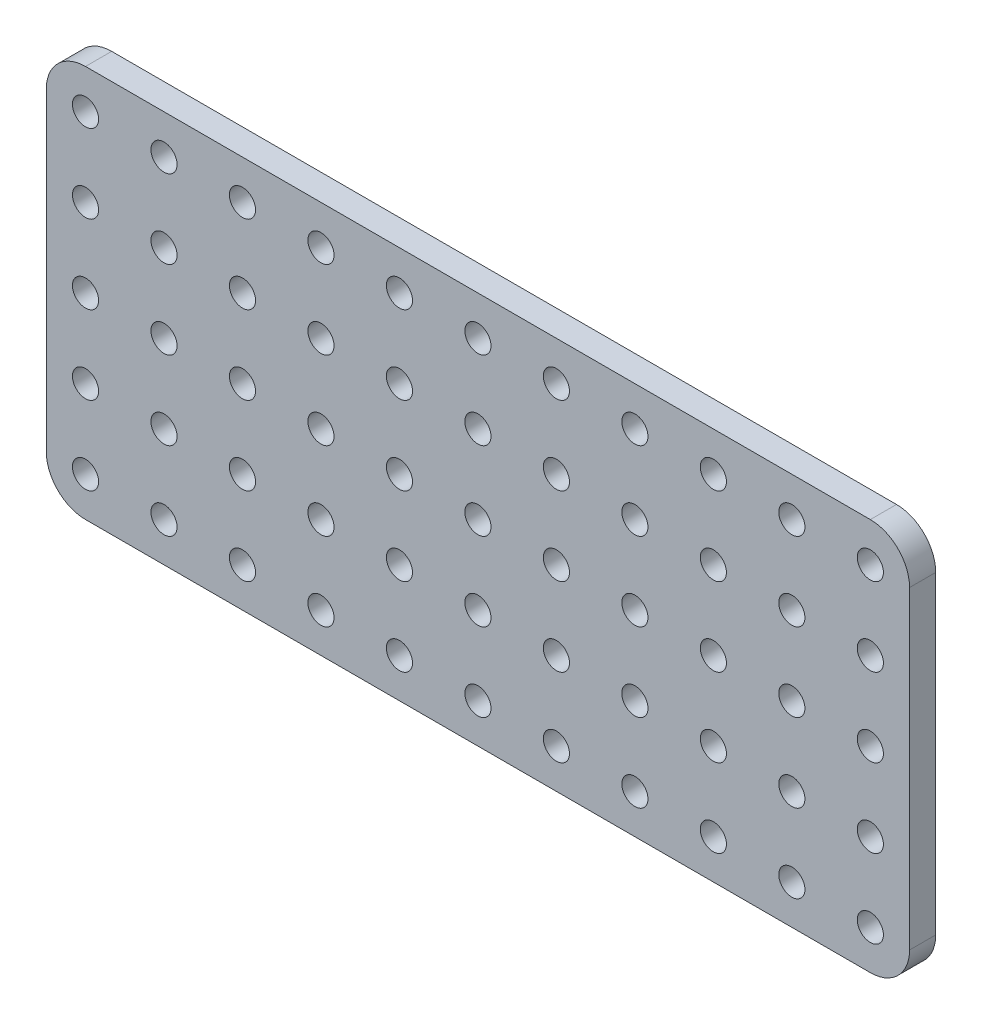
SolidWorks part; units mm, degrees
ref_plane "Alzado" through (0, 0, 0) normal (0, 0, 1) x (1, 0, 0)
ref_plane "Planta" through (0, 0, 0) normal (0, 1, 0) x (1, 0, 0)
ref_plane "Vista lateral" through (0, 0, 0) normal (1, 0, 0) x (0, 0, -1)
sketch "Model" plane through (0, 0, 0) normal (0, 0, 1) x (1, 0, 0)
  line L0 (-105.9434, 101.0565) -> (-105.9434, 65.0565)
  line L1 (-101.4434, 60.5565) -> (-11.4434, 60.5565)
  line L2 (-6.9434, 65.0565) -> (-6.9434, 101.0565)
  line L3 (-11.4434, 105.5565) -> (-101.4434, 105.5565)
  circle A0 centre (-101.4434, 101.0565) radius 1.5
  circle A1 centre (-92.4434, 101.0565) radius 1.5
  circle A2 centre (-83.4434, 101.0565) radius 1.5
  circle A3 centre (-74.4434, 101.0565) radius 1.5
  circle A4 centre (-65.4434, 101.0565) radius 1.5
  circle A5 centre (-56.4434, 101.0565) radius 1.5
  circle A6 centre (-47.4434, 101.0565) radius 1.5
  circle A7 centre (-20.4434, 101.0565) radius 1.5
  circle A8 centre (-101.4434, 92.0565) radius 1.5
  circle A9 centre (-92.4434, 92.0565) radius 1.5
  circle A10 centre (-83.4434, 92.0565) radius 1.5
  circle A11 centre (-74.4434, 92.0565) radius 1.5
  circle A12 centre (-65.4434, 92.0565) radius 1.5
  circle A13 centre (-56.4434, 92.0565) radius 1.5
  circle A14 centre (-47.4434, 92.0565) radius 1.5
  circle A15 centre (-20.4434, 92.0565) radius 1.5
  circle A16 centre (-101.4434, 83.0565) radius 1.5
  circle A17 centre (-92.4434, 83.0565) radius 1.5
  circle A18 centre (-83.4434, 83.0565) radius 1.5
  circle A19 centre (-74.4434, 83.0565) radius 1.5
  circle A20 centre (-65.4434, 83.0565) radius 1.5
  circle A21 centre (-56.4434, 83.0565) radius 1.5
  circle A22 centre (-47.4434, 83.0565) radius 1.5
  circle A23 centre (-20.4434, 83.0565) radius 1.5
  circle A24 centre (-101.4434, 65.0565) radius 1.5
  circle A25 centre (-92.4434, 65.0565) radius 1.5
  circle A26 centre (-83.4434, 65.0565) radius 1.5
  circle A27 centre (-74.4434, 65.0565) radius 1.5
  circle A28 centre (-65.4434, 65.0565) radius 1.5
  circle A29 centre (-56.4434, 65.0565) radius 1.5
  circle A30 centre (-47.4434, 65.0565) radius 1.5
  circle A31 centre (-20.4434, 65.0565) radius 1.5
  arc A32 (-101.4434, 105.5565) -> (-105.9434, 101.0565) centre (-101.4434, 101.0565) ccw
  arc A33 (-6.9434, 101.0565) -> (-11.4434, 105.5565) centre (-11.4434, 101.0565) ccw
  arc A34 (-105.9434, 65.0565) -> (-101.4434, 60.5565) centre (-101.4434, 65.0565) ccw
  arc A35 (-11.4434, 60.5565) -> (-6.9434, 65.0565) centre (-11.4434, 65.0565) ccw
  circle A36 centre (-11.4434, 101.0565) radius 1.5
  circle A37 centre (-11.4434, 92.0565) radius 1.5
  circle A38 centre (-11.4434, 83.0565) radius 1.5
  circle A39 centre (-11.4434, 65.0565) radius 1.5
  circle A40 centre (-101.4434, 74.0565) radius 1.5
  circle A41 centre (-92.4434, 74.0565) radius 1.5
  circle A42 centre (-83.4434, 74.0565) radius 1.5
  circle A43 centre (-74.4434, 74.0565) radius 1.5
  circle A44 centre (-65.4434, 74.0565) radius 1.5
  circle A45 centre (-56.4434, 74.0565) radius 1.5
  circle A46 centre (-47.4434, 74.0565) radius 1.5
  circle A47 centre (-20.4434, 74.0565) radius 1.5
  circle A48 centre (-11.4434, 74.0565) radius 1.5
  circle A49 centre (-38.4434, 101.0565) radius 1.5
  circle A50 centre (-29.4434, 101.0565) radius 1.5
  circle A51 centre (-38.4434, 92.0565) radius 1.5
  circle A52 centre (-29.4434, 92.0565) radius 1.5
  circle A53 centre (-38.4434, 83.0565) radius 1.5
  circle A54 centre (-29.4434, 83.0565) radius 1.5
  circle A55 centre (-38.4434, 65.0565) radius 1.5
  circle A56 centre (-29.4434, 65.0565) radius 1.5
  circle A57 centre (-38.4434, 74.0565) radius 1.5
  circle A58 centre (-29.4434, 74.0565) radius 1.5
extrude "Saliente-Extruir1" add sketch "Model" along normal blind 3
